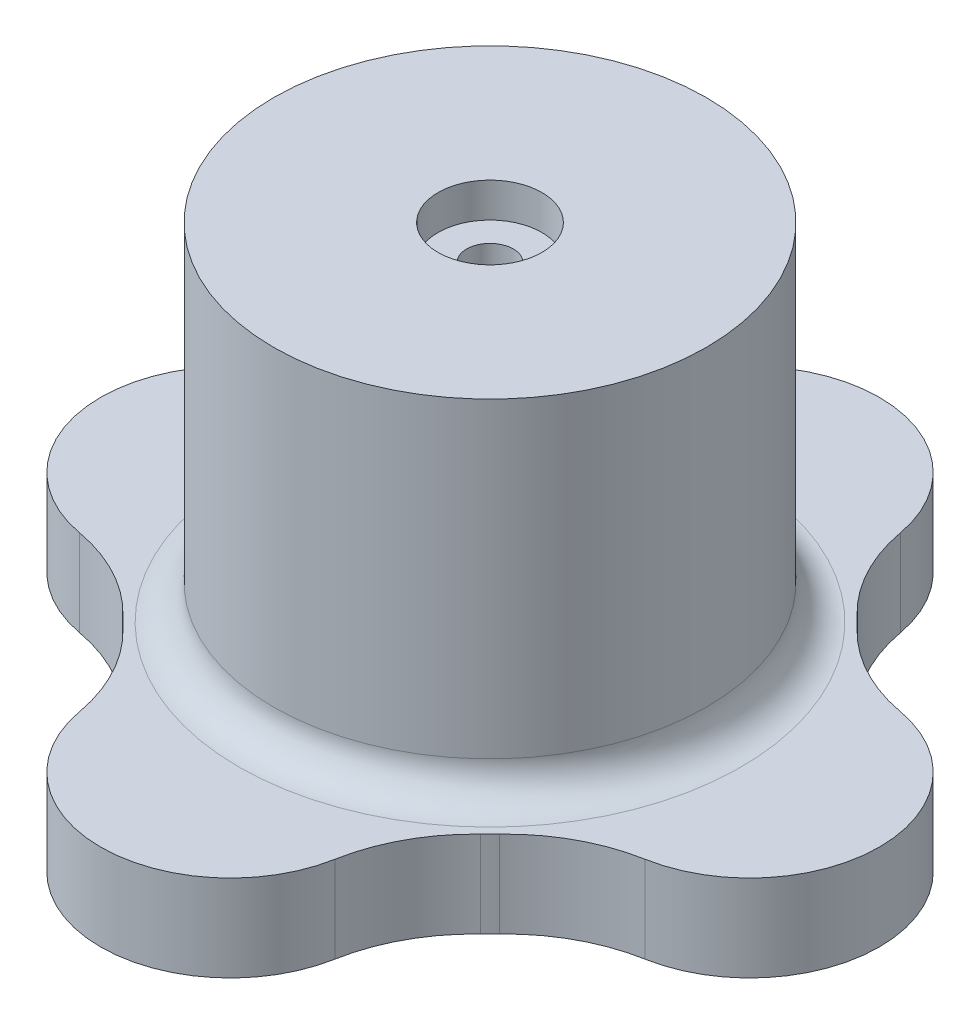
SolidWorks part; units mm, degrees
ref_plane "Front Plane" through (0, 0, 0) normal (0, 0, 1) x (1, 0, 0)
ref_plane "Top Plane" through (0, 0, 0) normal (0, 1, 0) x (1, 0, 0)
ref_plane "Right Plane" through (0, 0, 0) normal (1, 0, 0) x (0, 0, -1)
sketch "Sketch2" plane through (0, 0, 0) normal (0, 1, 0) x (1, 0, 0)
  arc A0 (-13.125, -7.2618) -> (-7.2618, -13.125) centre (0, 0) ccw
  arc A1 (-13.125, 7.2618) -> (-13.125, -7.2618) centre (-15, 0) ccw
  arc A2 (7.2618, 13.125) -> (-7.2618, 13.125) centre (0, 15) ccw
  arc A3 (13.125, -7.2618) -> (13.125, 7.2618) centre (15, 0) ccw
  arc A4 (-7.2618, -13.125) -> (7.2618, -13.125) centre (0, -15) ccw
  arc A5 (-7.2618, 13.125) -> (-13.125, 7.2618) centre (0, 0) ccw
  arc A6 (13.125, 7.2618) -> (7.2618, 13.125) centre (0, 0) ccw
  arc A7 (7.2618, -13.125) -> (13.125, -7.2618) centre (0, 0) ccw
  point P14 (0, 0)
  dimension "D1" = 30
  dimension "D2" = 15
  dimension "D3" = 4
extrude "Boss-Extrude1" add sketch "Sketch2" along normal blind 5 contours A4 A7 A3 A6 A2 A5 A1 A0
fillet "Fillet1" radius 10 8 edges at (7.2618, 2.5, -13.125) (13.125, 2.5, -7.2618) (7.2618, 2.5, 13.125) (13.125, 2.5, 7.2618) (-7.2618, 2.5, -13.125) (-13.125, 2.5, -7.2618) (-7.2618, 2.5, 13.125) (-13.125, 2.5, 7.2618)
sketch "Sketch3" plane through (0, 5, 0) normal (0, 1, 0) x (1, 0, 0)
  circle A0 centre (0, 0) radius 12.5
  dimension "D1" = 25
extrude "Boss-Extrude2" add sketch "Sketch3" along normal blind 20
sketch "Sketch4" plane through (0, 25, 0) normal (0, 1, 0) x (1, 0, 0)
  circle A0 centre (0, 0) radius 1.35
  dimension "D1" = 2.7
extrude "Cut-Extrude1" cut sketch "Sketch4" against normal blind 20
sketch "Sketch5" plane through (0, 25, 0) normal (0, 1, 0) x (1, 0, 0)
  circle A0 centre (0, 0) radius 3
  dimension "D1" = 6
extrude "Cut-Extrude2" cut sketch "Sketch5" against normal blind 2
fillet "Fillet3" radius 2 1 edges at (0, 5, 12.5)
